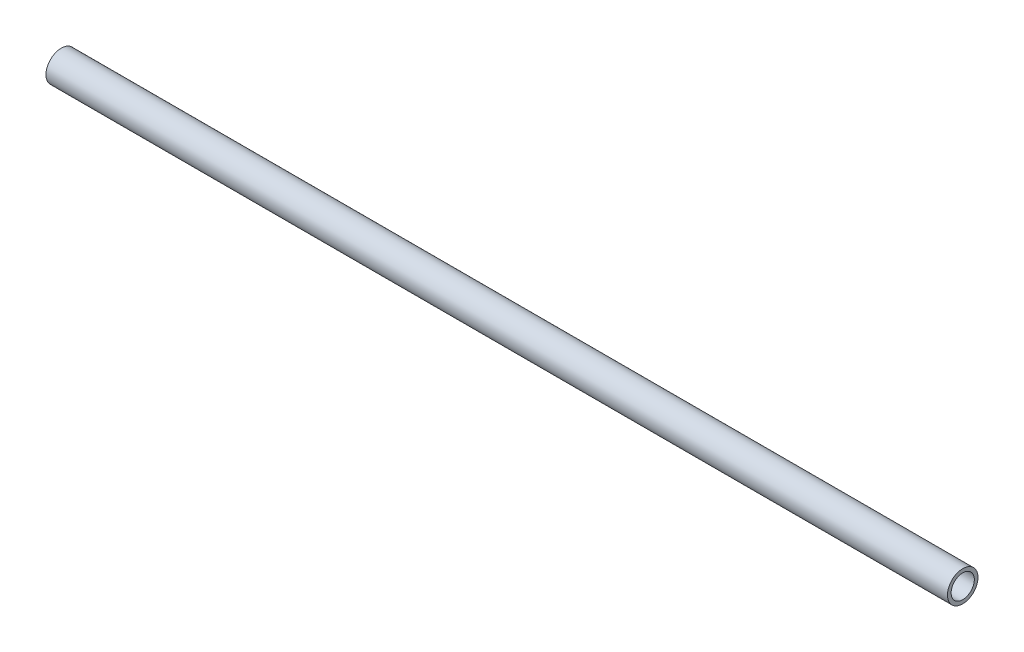
SolidWorks part; units mm, degrees
material "AISI 4130 Steel, annealed at 865C"
ref_plane "Front Plane" through (0, 0, 0) normal (0, 0, 1) x (1, 0, 0)
ref_plane "Top Plane" through (0, 0, 0) normal (0, 1, 0) x (1, 0, 0)
ref_plane "Right Plane" through (0, 0, 0) normal (1, 0, 0) x (0, 0, -1)
sketch "Sketch1" plane through (0, 0, 0) normal (1, 0, 0) x (0, 0, -1)
  circle A0 centre (0, 0) radius 12.7
  circle A1 centre (0, 0) radius 9.652
  dimension "D1" = 25.4
  dimension "D2" = 19.304
extrude "Boss-Extrude1" add sketch "Sketch1" along normal blind 750
